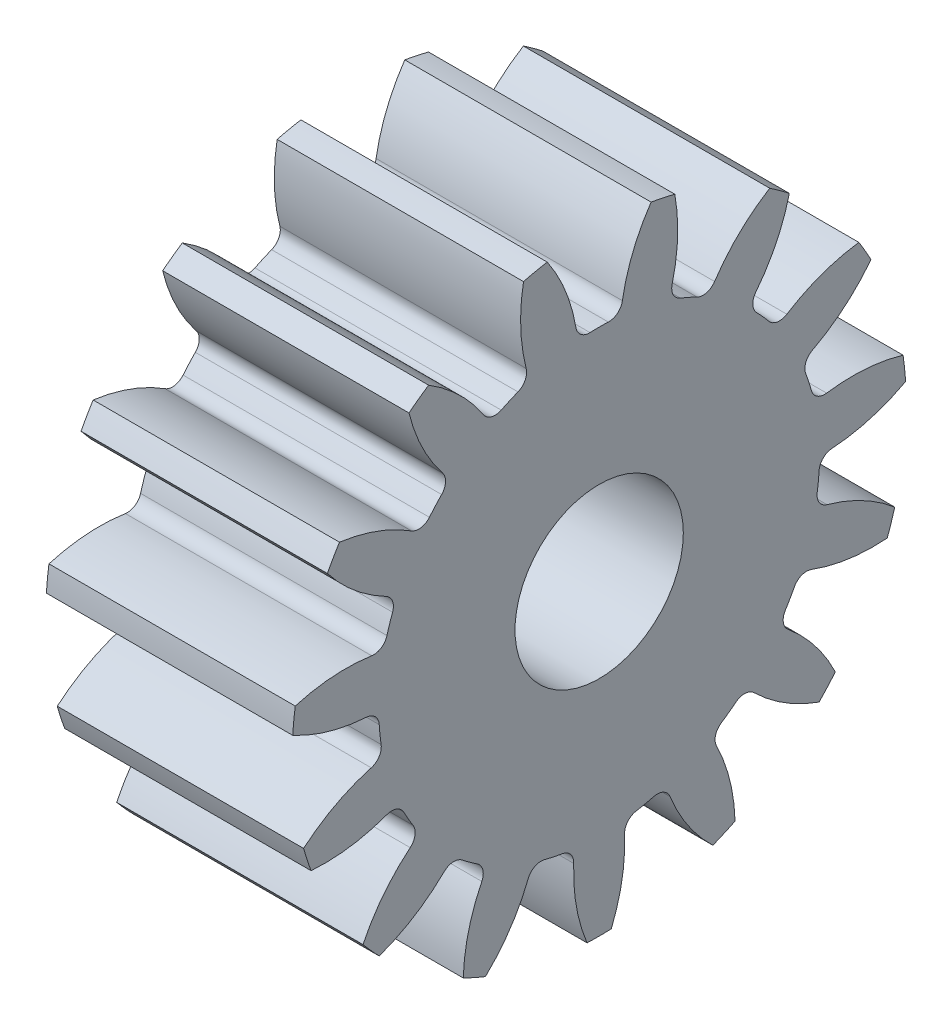
SolidWorks part; units mm, degrees
ref_plane "Front Plane" through (0, 0, 0) normal (0, 0, 1) x (1, 0, 0)
ref_plane "Top Plane" through (0, 0, 0) normal (0, 1, 0) x (1, 0, 0)
ref_plane "Right Plane" through (0, 0, 0) normal (1, 0, 0) x (0, 0, -1)
sketch "Sketch1" plane through (0, 0, 0) normal (1, 0, 0) x (0, 0, -1)
  circle A0 centre (0, 0) radius 2.5625
  circle A1 centre (0, 0) radius 9.35
  dimension "D1" = 5.125
  dimension "10mm" = 18.7
extrude "Boss-Extrude2" add sketch "Sketch1" along normal blind 7.5
sketch "Sketch3" plane through (7.5, 0, 0) normal (1, 0, 0) x (0, 0, -1)
  line L0 (0, 0) -> (0, 9.35) construction
  line L1 (-0.6576, 6.6777) -> (0, 0) construction
  line L2 (0, 5.3687) -> (-5.4415, 20.3191) construction
  circle A0 centre (0, 0) radius 9.35 construction
  arc A1 (0.6576, 6.6777) -> (-0.6576, 6.6777) centre (0, 0) ccw
  arc A2 (1.0289, 8.1856) -> (-1.0289, 8.1856) centre (0, 0) ccw construction
  arc A3 (1.5813, 9.2153) -> (-1.5813, 9.2153) centre (0, 0) ccw
  arc A4 (-1.5813, 9.2153) -> (-0.6576, 6.6777) centre (-6.07, 6.1447) cw
  arc A5 (1.5813, 9.2153) -> (0.6576, 6.6777) centre (6.07, 6.1447) ccw
  point P17 (-0.9594, 8.0047)
  dimension "D1" = 18.7
  dimension "D2" = 16.5
  dimension "D3" = 2.64
  dimension "D4" = 20
  dimension "D5" = 2.0579
extrude "Cut-Extrude1" cut sketch "Sketch3" against normal through all
fillet "Fillet1" radius 0.418 2 edges at (3.75, 6.6777, -0.6576) (3.75, 6.6777, 0.6576)
pattern_circular "CirPattern2" count 15 over 360 about axis through (0, 0, 0) along (1, 0, 0) of "Fillet1", "Cut-Extrude1"
ref_plane "Plane1" through (0, -7.4553, 5.4166) normal (0, 0.809, -0.5878) x (1, 0, 0)
sketch "Sketch4" plane through (0, -7.4553, 5.4166) normal (0, 0.809, -0.5878) x (1, 0, 0)
  line L0 (7.5, 0) -> (0, 0) construction
  line L1 (0, 0.2782) -> (0, -0.2782) construction
  line L2 (7.5, -0.2782) -> (7.5, 0.2782) construction
  circle A0 centre (3.75, 0) radius 1.5875
  point P4 (0, 0)
  point P7 (0, 0)
  point P10 (0, 0)
  point P11 (0, 0)
  point P12 (0, 0)
  point P13 (3.75, 0)
  dimension "D1" = 3.175
extrude "Cut-Extrude2" cut sketch "Sketch4" along normal up to surface (7.2038 mm away)
equation "\"No of teeth\"= 15"
equation "\"Module\"= 1.1"
equation "\"Outer Diameter\"= ( \"No of teeth\" + 2 ) * \"Module\""
equation "\"Pitch Diameter\"= \"No of teeth\" * \"Module\""
equation "\"Backlash\"= 0.3 * \"Module\""
equation "\"Arc Length\"= ( ( \"Module\" * pi ) / 2 ) + \"Backlash\""
equation "\"Fillet Radius\"= 0.38 * \"Module\""
equation "\"Bore Diameter\"= 5.125mm"
equation "\"Presseure angle\"= 20"
equation "\"Tooth Depth\"= IIF ( \"Module\" <= 1.25 , 2.4 * \"Module\" , 2.25 * \"Module\" )"
equation "\"D1@Sketch1\"=\"Bore Diameter\""
equation "\"10mm@Sketch1\" = \"Outer Diameter\""
equation "\"D1@Sketch3\"=\"Outer Diameter\""
equation "\"D2@Sketch3\"=\"Pitch Diameter\""
equation "\"D3@Sketch3\"=\"Tooth Depth\""
equation "\"D4@Sketch3\"=\"Presseure angle\""
equation "\"D5@Sketch3\"=\"Arc Length\""
equation "\"D1@Fillet1\"=\"Fillet Radius\""
equation "\"D1@CirPattern2\"=\"No of teeth\""
